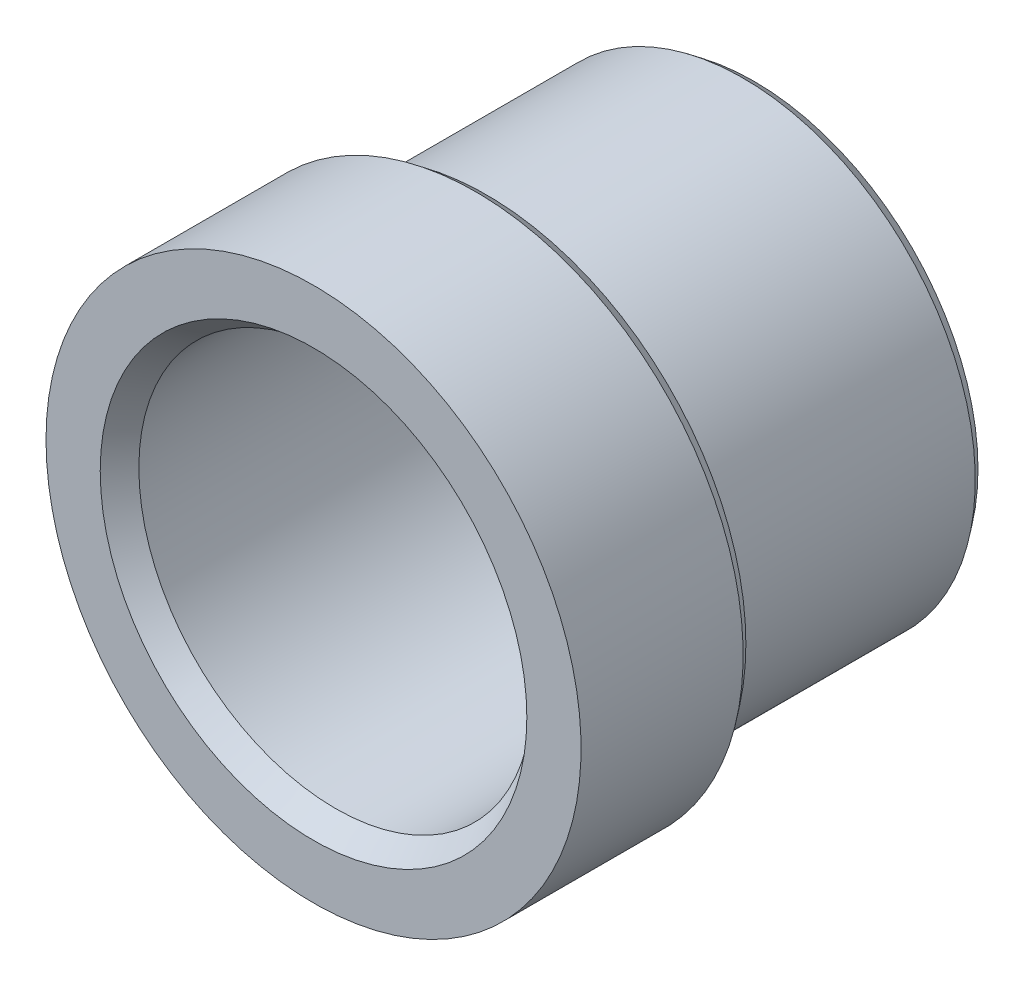
SolidWorks part; units mm, degrees
ref_plane "Front" through (0, 0, 0) normal (0, 0, 1) x (1, 0, 0)
ref_plane "Top" through (0, 0, 0) normal (0, 1, 0) x (1, 0, 0)
ref_plane "Right" through (0, 0, 0) normal (1, 0, 0) x (0, 0, -1)
sketch "Sketch1" plane through (0, 0, 0) normal (1, 0, 0) x (0, 0, -1)
  line L1 (7.112, 6.35) -> (7.112, 7.493)
  line L2 (7.112, 7.493) -> (-1.524, 7.493)
  line L3 (-1.524, 7.493) -> (-1.524, 8.636)
  line L4 (-1.524, 8.636) -> (-7.112, 8.636)
  line L5 (-7.112, 8.636) -> (-7.112, 6.35)
  line L6 (-7.112, 6.35) -> (7.112, 6.35)
  line L7 (7.112, 0) -> (-7.112, 0) construction
  dimension "Length [L]" = 14.224
  dimension "Flange Length [L1]" = 5.588
  dimension "Flange OD [X]" = 17.272
  dimension "For Tube OD" = 12.7
sketch "Sketch2" plane through (0, 0, 0) normal (1, 0, 0) x (0, 0, -1)
  line L0 (7.112, 6.35) -> (7.112, 7.493) construction
  line L1 (-7.112, 6.35) -> (7.112, 6.35) construction
  line L3 (-7.112, 8.636) -> (-7.112, 6.35) construction
  line L4 (-1.524, 8.636) -> (-7.112, 8.636) construction
  line L5 (-1.524, 7.493) -> (-1.524, 8.636) construction
  line L6 (7.112, 7.493) -> (-1.524, 7.493) construction
  line L7 (7.112, 6.35) -> (7.112, 7.493)
  line L8 (-7.112, 6.35) -> (7.112, 6.35)
  line L10 (-7.112, 8.636) -> (-7.112, 6.35)
  line L11 (-1.524, 8.636) -> (-7.112, 8.636)
  line L12 (-1.524, 7.493) -> (-1.524, 8.636)
  line L13 (7.112, 7.493) -> (-1.524, 7.493)
revolve "Revolve1" add sketch "Sketch2" angle 360 about L7
chamfer "Chamfer1" distance 0.7112 angle 37 1 edges at (-6.35, 0, 7.112)
chamfer "Chamfer2" distance 0.3556 angle 37 2 edges at (-7.493, 0, -7.112) (-8.636, 0, 1.524)
equation "\"D1@Chamfer1\"=\"For Tube OD@Sketch1\"*.056"
equation "\"D1@Chamfer2\"=\"For Tube OD@Sketch1\"*.028"
